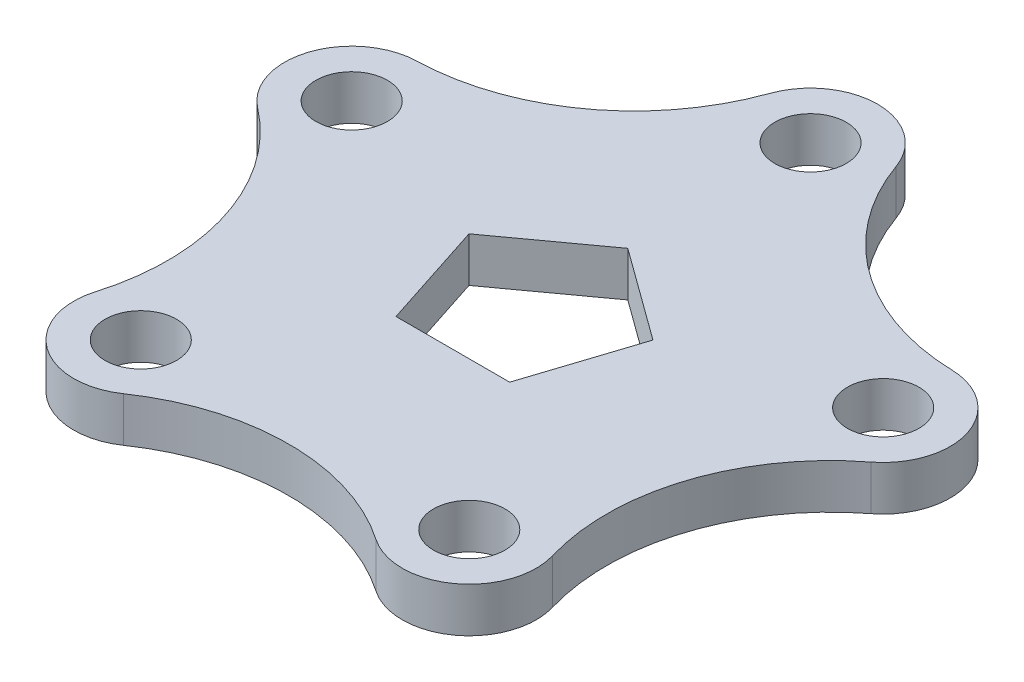
SolidWorks part; units mm, degrees
ref_plane "Front Plane" through (0, 0, 0) normal (0, 0, 1) x (1, 0, 0)
ref_plane "Top Plane" through (0, 0, 0) normal (0, 1, 0) x (1, 0, 0)
ref_plane "Right Plane" through (0, 0, 0) normal (1, 0, 0) x (0, 0, -1)
sketch "Sketch1" plane through (0, 0, 0) normal (0, 1, 0) x (1, 0, 0)
  line L1 (0, 21.6312) -> (-20.5725, 6.6844)
  line L2 (-20.5725, 6.6844) -> (-12.7145, -17.5)
  line L3 (-12.7145, -17.5) -> (12.7145, -17.5)
  line L4 (12.7145, -17.5) -> (20.5725, 6.6844)
  line L5 (20.5725, 6.6844) -> (0, 21.6312)
  circle A0 centre (0, 0) radius 17.5 construction
  circle A1 centre (59.441, 19.3136) radius 8
  circle A2 centre (0, 62.5) radius 8
  circle A4 centre (36.7366, -50.5636) radius 8
  circle A5 centre (-36.7366, -50.5636) radius 8
  circle A6 centre (-59.441, 19.3136) radius 8
  circle A7 centre (0, 0) radius 62.5 construction
  circle A8 centre (0, 62.5) radius 15
  circle A9 centre (59.441, 19.3136) radius 15
  circle A10 centre (36.7366, -50.5636) radius 15
  circle A11 centre (-36.7366, -50.5636) radius 15
  circle A12 centre (-59.441, 19.3136) radius 15
  arc A13 (14.1321, 67.5282) -> (59.856, 34.3078) centre (61.2393, 84.2887) ccw
  arc A14 (68.5902, 7.4269) -> (51.1252, -46.3248) centre (99.0873, -32.1954) ccw
  arc A15 (28.2589, -62.9381) -> (-28.2589, -62.9381) centre (0, -104.1865) ccw
  arc A16 (-51.1252, -46.3248) -> (-68.5902, 7.4269) centre (-99.0873, -32.1954) ccw
  arc A17 (-59.856, 34.3078) -> (-14.1321, 67.5282) centre (-61.2393, 84.2887) ccw
  point P21 (0, 0)
  point P31 (0, 0)
  point P47 (0, 0)
  dimension "D1" = 35
  dimension "D2" = 5
  dimension "D3" = 16
  dimension "D4" = 30
  dimension "D5" = 5
  dimension "D6" = 50
  dimension "D7" = 5
extrude "Boss-Extrude1" add sketch "Sketch1" along normal blind 10 contours A17 A12 A16 A11 A15 A10 A14 A9 A13 A8 L5 L4 L3 L2 L1 | A11 A5 | A10 A4 | A9 A1 | A8 A2 | A12 A6
